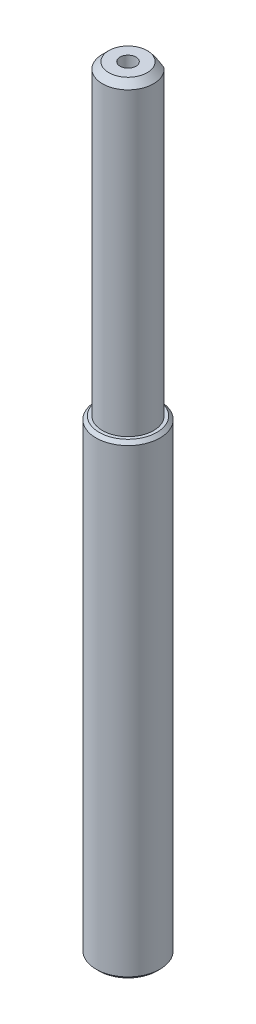
SolidWorks part; units mm, degrees
material "Acier allié inoxydable"
ref_plane "Face" through (0, 0, 0) normal (0, 0, 1) x (1, 0, 0)
ref_plane "Dessus" through (0, 0, 0) normal (0, 1, 0) x (1, 0, 0)
ref_plane "Droite" through (0, 0, 0) normal (1, 0, 0) x (0, 0, -1)
sketch "Esquisse1" plane through (0, 0, 0) normal (0, 1, 0) x (1, 0, 0)
  circle A0 centre (0, 0) radius 2
  dimension "D1" = 4
extrude "Boss.-Extru.1" add sketch "Esquisse1" along normal blind 24
sketch "Esquisse2" plane through (0, 0, 0) normal (0, -1, 0) x (1, 0, 0)
  circle A0 centre (0, 0) radius 2.5
  dimension "D1" = 5
extrude "Boss.-Extru.2" add sketch "Esquisse2" along normal blind 36.5
chamfer "Chanfrein1" distance 0.5 angle 45 1 edges at (0, 24, 2)
hole_wizard "Trou taraudé M1.61" positions "Esquisse4" profile "Esquisse3" tap size "M1.6" standard "Iso"
sketch "Esquisse4" plane through (0, 24, 0) normal (0, 1, 0) x (1, 0, 0)
  point P0 (0, 0)
sketch "Esquisse3" plane through (0, 24, 0) normal (1, 0, 0) x (0, 0, 1)
  line L0 (0, 0) -> (0, 5.3255)
  line L1 (0, 5.3255) -> (0.625, 4.95)
  line L2 (0.625, 4.95) -> (0.625, 0)
  line L5 (0.625, 0) -> (0, 0)
  line L10 (0, 5.3255) -> (-0.625, 4.95) construction
  line L11 (0, -6.35) -> (0, 107.95) construction
  dimension "Diamètre du trou pour taraudage" = 1.25
  dimension "Profondeur du trou pour taraudage" = 4.95
  dimension "Angle de pointe" = 118
cosmetic thread "Filetage de perçage1" parameters "D1"=3.2, "D2"=1.6
sketch "Esquisse5" plane through (0, 24, 0) normal (0, 1, 0) x (1, 0, 0)
  line L0 (-1.3229, 1.5) -> (1.3229, 1.5)
  circle A0 centre (0, 0) radius 2 construction
  arc A1 (1.3229, 1.5) -> (-1.3229, 1.5) centre (0, 0) ccw
  dimension "D1" = 3.5
extrude "Enlèv. mat.-Extru.1" cut sketch "Esquisse5" against normal blind 15
chamfer "Chanfrein2" distance 0.25 angle 45 2 edges at (0, 0, -2.5) (0, -36.5, -2.5)
ref_plane "Plan pour Y" through (0, 18.7, 0) normal (0, 1, 0) x (1, 0, 0)
ref_plane "Plan pour X" through (0, 14, 0) normal (0, 1, 0) x (1, 0, 0)
